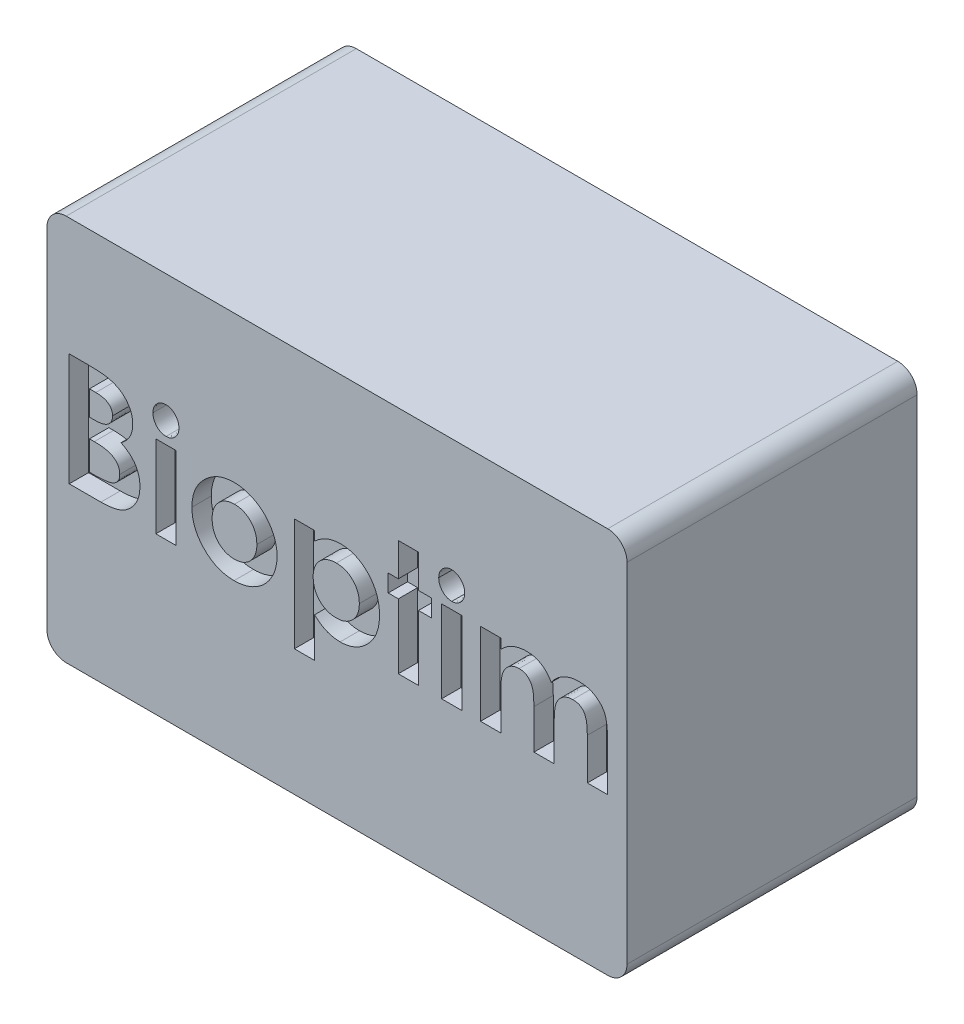
SolidWorks part; units mm, degrees
ref_plane "Plan de face" through (0, 0, 0) normal (0, 0, 1) x (1, 0, 0)
ref_plane "Plan de dessus" through (0, 0, 0) normal (0, 1, 0) x (1, 0, 0)
ref_plane "Plan de droite" through (0, 0, 0) normal (1, 0, 0) x (0, 0, -1)
sketch "Esquisse1" plane through (0, 0, 0) normal (0, 0, 1) x (1, 0, 0)
  line L1 (-150, -100) -> (150, -100)
  line L2 (-150, -100) -> (-150, 100)
  line L3 (-150, 100) -> (150, 100)
  line L4 (150, -100) -> (150, 100)
  line L5 (-150, -100) -> (150, 100) construction
  line L6 (-150, 100) -> (150, -100) construction
  point P0 (0, 0)
  dimension "D1" = 200
  dimension "D2" = 300
extrude "Boss.-Extru.1" add sketch "Esquisse1" along normal mid plane 150
sketch "Esquisse3" plane through (0, 0, 75) normal (0, 0, 1) x (1, 0, 0)
  line L0 (-150, -19.0955) -> (150, -19.0955) construction
  line L3 (-150, 100) -> (-150, -100) construction
  line L4 (150, -100) -> (150, 100) construction
  text T0 "Bioptim" font "Century Gothic" height in points 220
  point P3 (-72.2242, 0)
  point P4 (0, 0)
  point P7 (0, 0)
  point P8 (0, 0)
  point P9 (150, -19.0955)
  dimension "D1" = 20
extrude "Enlèv. mat.-Extru.1" cut sketch "Esquisse3" against normal blind 10
fillet "Congé1" radius 10 4 edges at (150, -100, 0) (-150, -100, 0) (-150, 100, 0) (150, 100, 0)
sketch "Esquisse5" plane through (0, 100, 0) normal (0, 1, 0) x (1, 0, 0)
  line L0 (-150, 0) -> (0, 0) construction
  line L1 (-150, -75) -> (-150, 75) construction
  line L3 (-90, -15) -> (-60, -15)
  line L4 (-90, -15) -> (-90, 15)
  line L5 (-90, 15) -> (-60, 15)
  line L6 (-60, -15) -> (-60, 15)
  line L7 (-90, -15) -> (-60, 15) construction
  line L8 (-90, 15) -> (-60, -15) construction
  circle A0 centre (-75, 0) radius 15
  point P3 (-75, 0)
  dimension "D1" = 30
  dimension "D2" = 30
  dimension "D3" = 30
